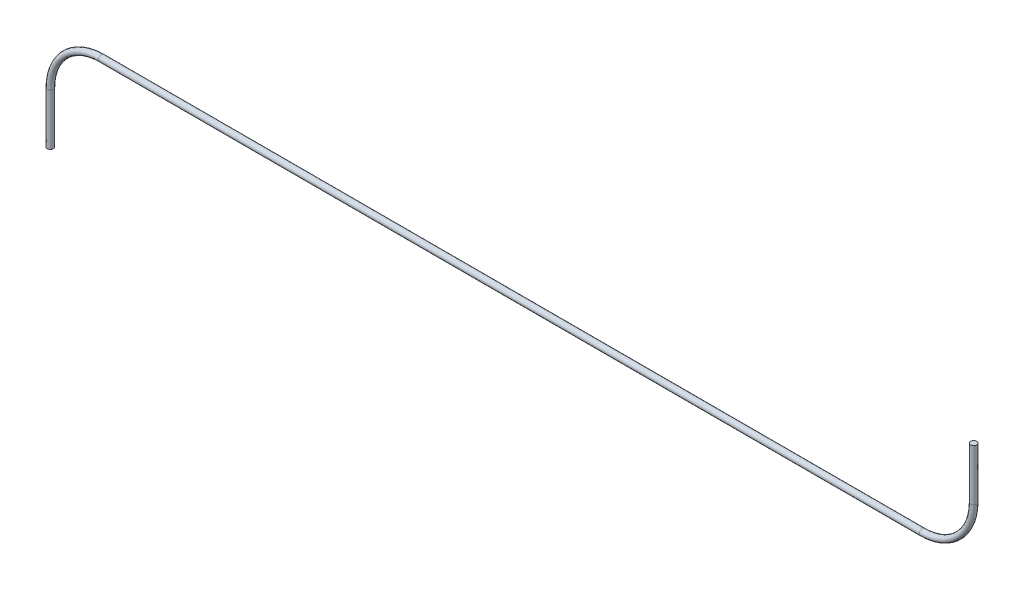
SolidWorks part; units mm, degrees
ref_plane "Front Plane" through (0, 0, 0) normal (0, 0, 1) x (1, 0, 0)
ref_plane "Top Plane" through (0, 0, 0) normal (0, 1, 0) x (1, 0, 0)
ref_plane "Right Plane" through (0, 0, 0) normal (1, 0, 0) x (0, 0, -1)
sketch "Sketch1" plane through (0, 0, 0) normal (0, 0, 1) x (1, 0, 0)
  line L0 (0, 0) -> (0, 10)
  line L1 (10, 20) -> (170, 20)
  line L2 (180, 30) -> (180, 40)
  arc A0 (170, 20) -> (180, 30) centre (170, 30) ccw
  arc A1 (0, 10) -> (10, 20) centre (10, 10) cw
  point P7 (180, 20)
  point P10 (0, 20)
  dimension "D4" = 10
  dimension "D1" = 180
  dimension "D2" = 20
  dimension "D3" = 20
sweep "Sweep1" add path "Sketch1" circular profile diameter 1.2 parameters "D3"=1.2
